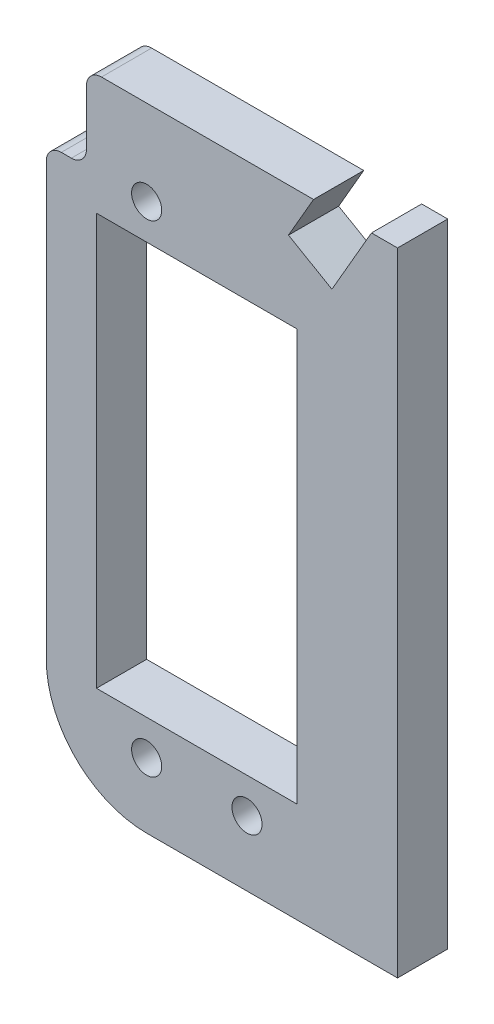
SolidWorks part; units mm, degrees
ref_plane "Plan de face" through (0, 0, 0) normal (0, 0, 1) x (1, 0, 0)
ref_plane "Plan de dessus" through (0, 0, 0) normal (0, 1, 0) x (1, 0, 0)
ref_plane "Plan de droite" through (0, 0, 0) normal (1, 0, 0) x (0, 0, -1)
sketch "Esquisse1" plane through (0, 0, 0) normal (0, 0, 1) x (1, 0, 0)
  line L0 (15, 10) -> (15, 51) construction
  line L1 (0, 0) -> (25, 0)
  line L2 (0, 0) -> (0, 54.5)
  line L3 (4, 63) -> (26.632, 63)
  line L4 (32.4055, 63) -> (28.4621, 56.1699)
  line L5 (15, 51) -> (5, 51)
  line L6 (15, 63) -> (32.4055, 63)
  line L7 (25, 10) -> (5, 10)
  line L8 (5, 51) -> (5, 10)
  line L9 (5, 30.5) -> (25, 30.5) construction
  line L10 (25, 10) -> (25, 51)
  line L11 (25, 51) -> (15, 51)
  line L12 (25, 0) -> (35, 0)
  line L13 (35, 0) -> (35, 63)
  line L14 (31.0278, 60.6138) -> (27.2778, 54.1186) construction
  line L15 (28.4621, 56.1699) -> (24.132, 58.6699)
  line L16 (24.132, 58.6699) -> (26.632, 63)
  line L17 (32.4055, 63) -> (35, 63)
  line L18 (32.4055, 63) -> (15, 63)
  line L22 (0, 54.5) -> (4, 54.5)
  line L23 (4, 63) -> (4, 54.5)
  circle A0 centre (10, 54.5) radius 1.5
  circle A1 centre (20, 54.5) radius 1.5 construction
  circle A2 centre (20, 6.5) radius 1.5
  circle A3 centre (10, 6.5) radius 1.5
  dimension "D6" = 3.5
  dimension "D8" = 3
  dimension "D1" = 20
  dimension "D2" = 41
  dimension "D3" = 10
  dimension "D4" = 12
  dimension "D5" = 5
  dimension "D7" = 5
  dimension "D9" = 10
  dimension "D10" = 5
  dimension "D11" = 5
  dimension "D12" = 4
  dimension "D13" = 8.5
extrude "Boss.-Extru.1" add sketch "Esquisse1" along normal blind 5 contours L17 L6 L4 L15 L16 L3 L2 L1 L12 L13 L11 L10 L7 L8 L5 A0 A2 A3
fillet "Congé2" radius 10 1 edges at (0, 0, 2.5)
fillet "Congé4" radius 1.5 3 edges at (0, 54.5, 2.5) (4, 63, 2.5) (4, 54.5, 2.5)
